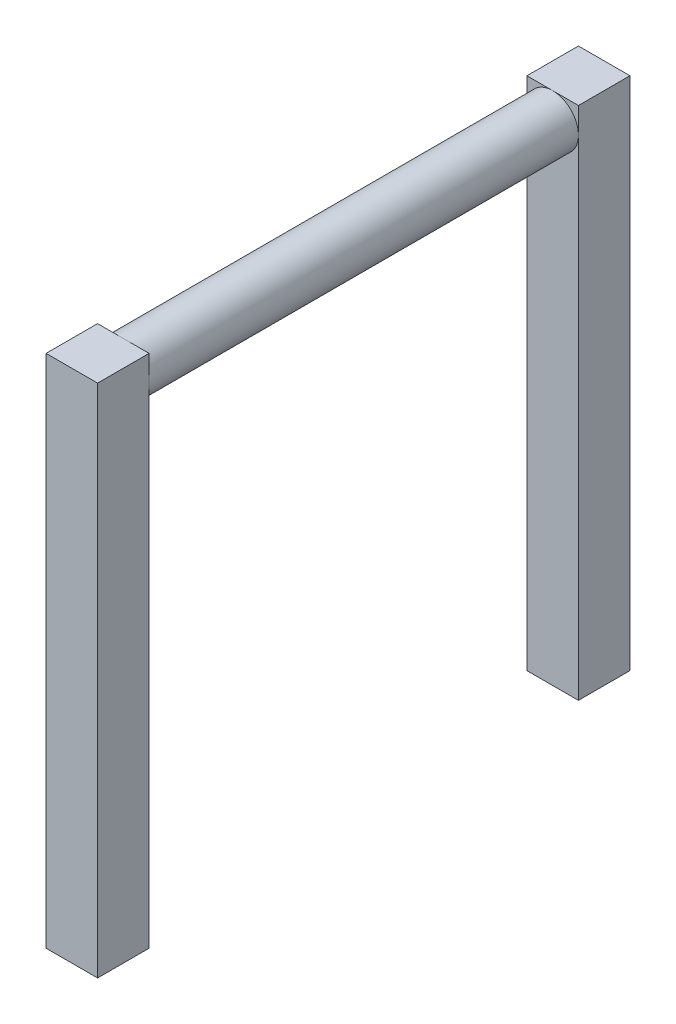
SolidWorks part; units mm, degrees
ref_plane "Front" through (0, 0, 0) normal (0, 0, 1) x (1, 0, 0)
ref_plane "Top" through (0, 0, 0) normal (0, 1, 0) x (1, 0, 0)
ref_plane "Right" through (0, 0, 0) normal (1, 0, 0) x (0, 0, -1)
sketch "Croquis1" plane through (0, 0, 0) normal (1, 0, 0) x (0, 0, -1)
  line L0 (56, 0) -> (62, 0)
  line L1 (0, 0) -> (6, 0)
  line L2 (0, 0) -> (0, 60)
  line L3 (0, 60) -> (6, 60)
  line L4 (62, 0) -> (62, 60)
  line L6 (6, 0) -> (6, 54)
  line L8 (56, 0) -> (56, 54)
  line L9 (6, 54) -> (6, 60)
  line L10 (56, 54) -> (56, 60)
  line L11 (56, 60) -> (62, 60)
  dimension "D1" = 62
  dimension "D2" = 6
  dimension "D3" = 6
  dimension "D5" = 60
extrude "Saliente-Extruir1" add sketch "Croquis1" along normal blind 6
sketch "Croquis2" plane through (0, 0, -56) normal (0, 0, 1) x (1, 0, 0)
  line L0 (3, 60) -> (3, 57) construction
  line L1 (6, 60) -> (0, 60) construction
  circle A0 centre (3, 57) radius 3
  dimension "D1" = 6
  dimension "D2" = 3
extrude "Saliente-Extruir2" add sketch "Croquis2" along normal up to next
